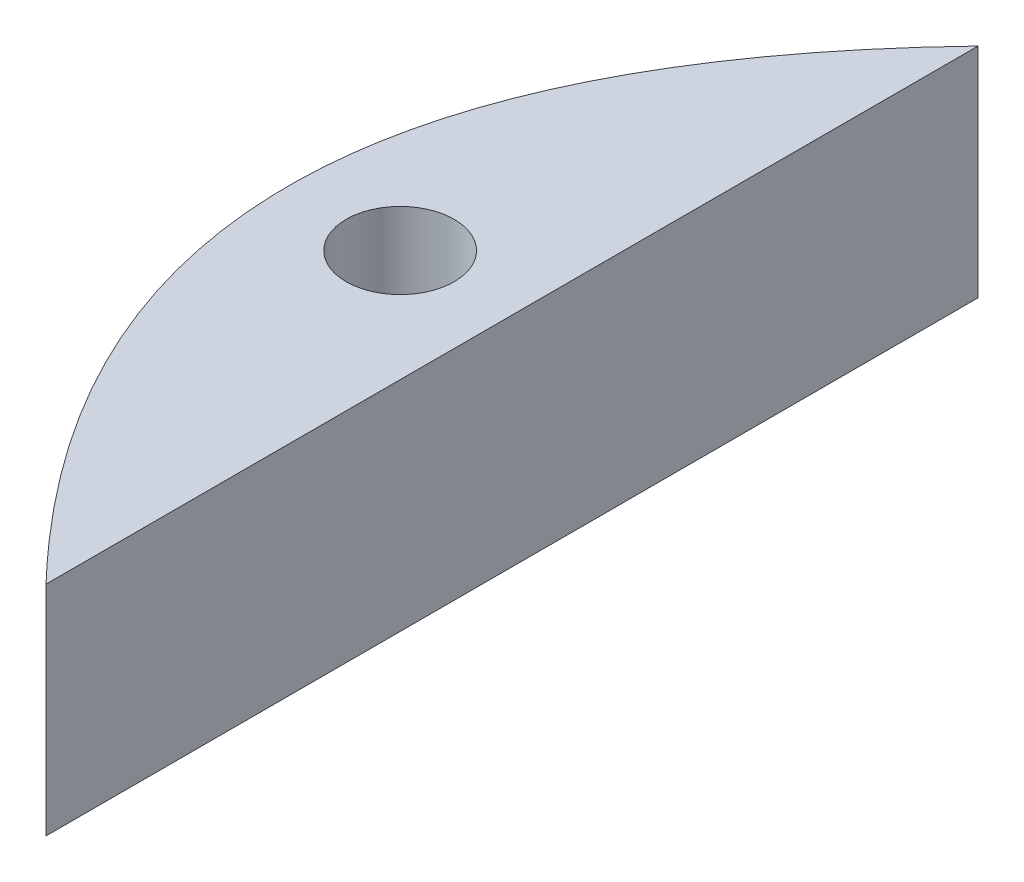
SolidWorks part; units mm, degrees
material "Acrylic (Medium-high impact)"
ref_plane "Front Plane" through (0, 0, 0) normal (0, 0, 1) x (1, 0, 0)
ref_plane "Top Plane" through (0, 0, 0) normal (0, 1, 0) x (1, 0, 0)
ref_plane "Right Plane" through (0, 0, 0) normal (1, 0, 0) x (0, 0, -1)
sketch "Sketch1" plane through (0, 0, 0) normal (0, 1, 0) x (1, 0, 0)
  line L0 (-1000, 0) -> (49000, 0) construction
  line L1 (0, -1000) -> (0, 49000) construction
  line L2 (3, 12.5) -> (3, -12.5)
  circle A0 centre (0, 0) radius 1.45
  spline S0 degree 2 poles (3, 12.5) (-9, 0) (3, -12.5) knots 0 0 0 1 1 1
  point P10 (1.45, 0)
  dimension "D1" = 2.9
  dimension "D4" = 3
  dimension "D2" = 3
  dimension "D3" = 25
extrude "Boss-Extrude1" add sketch "Sketch1" along normal blind 5.85
